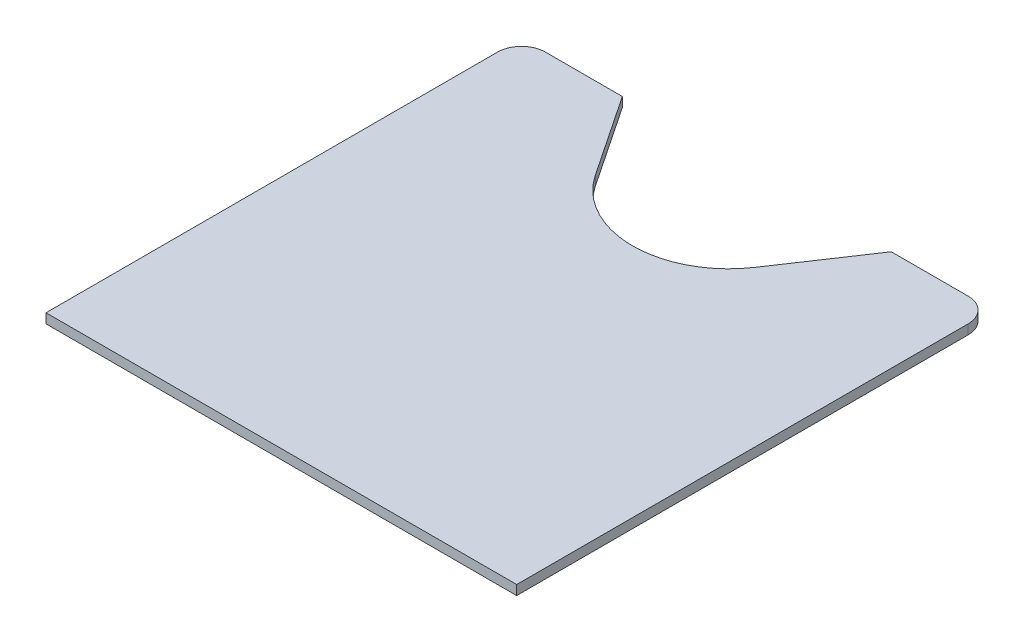
SolidWorks part; units mm, degrees
ref_plane "Ebene vorne" through (0, 0, 0) normal (0, 0, 1) x (1, 0, 0)
ref_plane "Ebene oben" through (0, 0, 0) normal (0, 1, 0) x (1, 0, 0)
ref_plane "Ebene rechts" through (0, 0, 0) normal (1, 0, 0) x (0, 0, -1)
sketch "Skizze2" plane through (0, 0, 0) normal (0, 1, 0) x (1, 0, 0)
  line L0 (0, 82.3632) -> (0, -81.2206) construction
  line L6 (-44, 50) -> (-28, 50)
  line L7 (-28, 50) -> (-16.6199, 33)
  line L8 (28, 50) -> (16.6199, 33)
  line L9 (44, 50) -> (28, 50)
  line L10 (-49, -49) -> (-49, 45)
  line L11 (49, -49) -> (49, 45)
  line L12 (-49, -49) -> (49, -49)
  arc A0 (-16.6199, 33) -> (16.6199, 33) centre (0, 44.1257) ccw
  arc A1 (49, 45) -> (44, 50) centre (44, 45) ccw
  arc A2 (-49, 45) -> (-44, 50) centre (-44, 45) cw
  point P0 (0, 0)
  point P3 (49, 50)
  point P16 (-49, 50)
  dimension "D1" = 20
  dimension "D8" = 5
  dimension "D2" = 49
  dimension "D3" = 99
  dimension "D4" = 21
  dimension "D5" = 17
  dimension "D6" = 49
  dimension "D7" = 49
extrude "Aufsatz-Linear austragen2" add sketch "Skizze2" along normal blind 2
